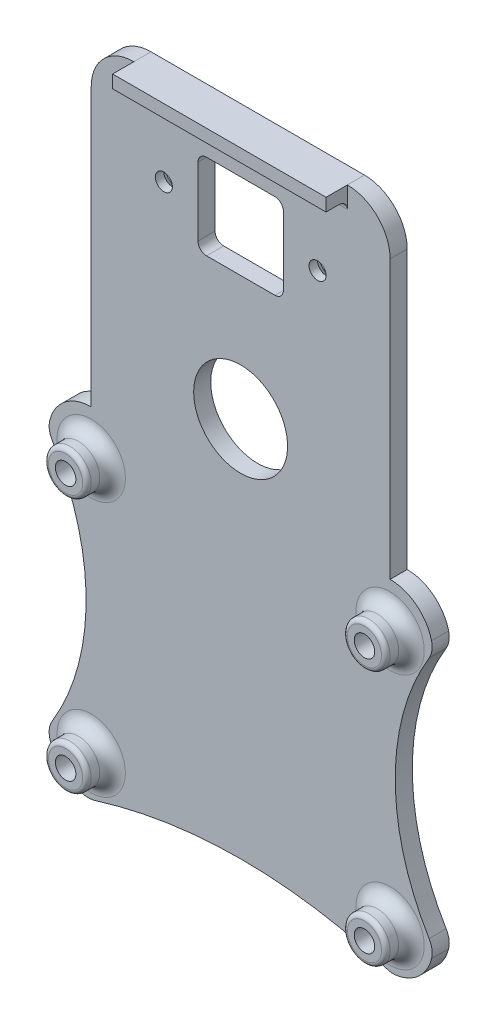
SolidWorks part; units mm, degrees
ref_plane "Front Plane" through (0, 0, 0) normal (0, 0, 1) x (1, 0, 0)
ref_plane "Top Plane" through (0, 0, 0) normal (0, 1, 0) x (1, 0, 0)
ref_plane "Right Plane" through (0, 0, 0) normal (1, 0, 0) x (0, 0, -1)
sketch "Sketch1" plane through (0, 0, 0) normal (0, 0, 1) x (1, 0, 0)
  line L0 (-35, -30.3) -> (35, -30.3) construction
  line L1 (-35, 29.5) -> (35, 29.5) construction
  line L2 (0, 40) -> (0, -55.1813) construction
  line L3 (-35, 40) -> (35, 40)
  circle A0 centre (-35, 29.5) radius 2.4
  circle A1 centre (35, 29.5) radius 2.4
  circle A2 centre (-35, -30.3) radius 2.4
  circle A3 centre (35, -30.3) radius 2.4
  arc A4 (35, 40) -> (45, 30) centre (35, 30) cw
  arc A5 (45, -29.6893) -> (35.245, -39.6893) centre (35, -29.6923) cw
  arc A6 (-35, -39.6893) -> (-45, -29.6893) centre (-35, -29.6893) cw
  arc A7 (-45, 30) -> (-35, 40) centre (-35, 30) cw
  arc A8 (-45, 30) -> (-45, -29.6893) centre (-91.1985, 0.1554) cw
  arc A9 (45, 30) -> (45, -29.6893) centre (91.1985, 0.1554) ccw
  arc A10 (-35, -39.6893) -> (35.245, -39.6893) centre (0.1225, -149.1946) cw
  point P0 (0, 0)
  point P6 (0, 0)
  point P18 (45, 40)
  dimension "D5" = 10
  dimension "D1" = 10.5
  dimension "D3" = 59.8
  dimension "D4" = 70
extrude "Boss-Extrude1" add sketch "Sketch1" along normal blind 4
sketch "Sketch2" plane through (0, 0, 4) normal (0, 0, 1) x (1, 0, 0)
  circle A0 centre (-35, 29.5) radius 5.0046
  circle A1 centre (35, 29.5) radius 5
  circle A2 centre (-35, -30.3) radius 5
  circle A3 centre (35, -30.3) radius 5
  circle A4 centre (-35, 29.5) radius 2.4
  circle A5 centre (35, 29.5) radius 2.4
  circle A6 centre (35, -30.3) radius 2.4
  circle A7 centre (-35, -30.3) radius 2.4
extrude "Boss-Extrude2" add sketch "Sketch2" along normal blind 6
chamfer "Chamfer1" [suppressed] distance 3 angle 45
fillet "Fillet1" radius 3 4 edges at (-40, -30.3, 4) (30, -30.3, 4) (30, 29.5, 4) (-40.0046, 29.5, 4)
fillet "Fillet2" radius 1 4 edges at (-30, -30.3, 10) (40, -30.3, 10) (40, 29.5, 10) (-29.9954, 29.5, 10)
fillet "Fillet3" radius 5 6 edges at (45, 30, 2) (45, -29.6893, 2) (35.245, -39.6893, 2) (-35, -39.6893, 2) (-45, -29.6893, 2) (-45, 30, 2)
sketch "Sketch3" plane through (0, 0, 0) normal (0, 0, -1) x (-1, 0, 0)
  line L0 (-35, 40) -> (35, 40) construction
  line B0 (-35, 40) -> (35, 40)
  line B1 (-35, 40) -> (-35, 105)
  line B2 (-25, 115) -> (25, 115)
  line B3 (35, 40) -> (35, 105)
  arc B4 (35, 105) -> (25, 115) centre (25, 105) ccw
  arc B5 (-25, 115) -> (-35, 105) centre (-25, 105) ccw
sketch_block_instance "Block1-1"
sketch_block "Block1"
extrude "Boss-Extrude3" add sketch "Sketch3" against normal blind 4
sketch "Sketch4" plane through (0, 0, 0) normal (0, 0, -1) x (-1, 0, 0)
  line L0 (0, 115) -> (-0.0863, -34.1946) construction
  line L1 (25, 115) -> (-25, 115) construction
  arc A0 (34.1514, -39.4207) -> (-34.3274, -39.3992) centre (-0.1225, -149.1946) ccw construction
  circle A1 centre (-18.0121, 94.13) radius 2
  circle A2 centre (17.9879, 94.13) radius 2
  line B0 (-8.0121, 84.13) -> (7.9879, 84.13)
  line B1 (-10.0121, 86.13) -> (-10.0121, 102.13)
  line B2 (-8.0121, 104.13) -> (7.9879, 104.13)
  line B3 (9.9879, 86.13) -> (9.9879, 102.13)
  line B4 (-10.0121, 84.13) -> (9.9879, 104.13) construction
  line B5 (-10.0121, 104.13) -> (9.9879, 84.13) construction
  arc B6 (-10.0121, 86.13) -> (-8.0121, 84.13) centre (-8.0121, 86.13) ccw
  arc B7 (7.9879, 84.13) -> (9.9879, 86.13) centre (7.9879, 86.13) ccw
  arc B8 (9.9879, 102.13) -> (7.9879, 104.13) centre (7.9879, 102.13) ccw
  arc B9 (-8.0121, 104.13) -> (-10.0121, 102.13) centre (-8.0121, 102.13) ccw
  circle B10 centre (0.0106, 54.9994) radius 11
  dimension "D2" = 18
  dimension "D1" = 10.87
  dimension "D3" = 18
sketch_block_instance "Block2-1"
sketch_block "Block2" parameters "D2"=2, "D1"=20
extrude "Cut-Extrude1" cut sketch "Sketch4" against normal up to next
chamfer "Chamfer2" distance 2 angle 45 2 edges at (16.0121, 94.13, 0) (-19.9879, 94.13, 0)
sketch "Sketch5" plane through (0, 0, 4) normal (0, 0, 1) x (1, 0, 0)
  line L1 (-25, 115) -> (25, 115)
  line L2 (-25, 115) -> (-25, 112)
  line L3 (-25, 112) -> (25, 112)
  line L4 (25, 115) -> (25, 112)
  dimension "D1" = 3
extrude "Boss-Extrude4" add sketch "Sketch5" along normal blind 5
fillet "Fillet4" radius 2 1 edges at (0, 112, 4)
